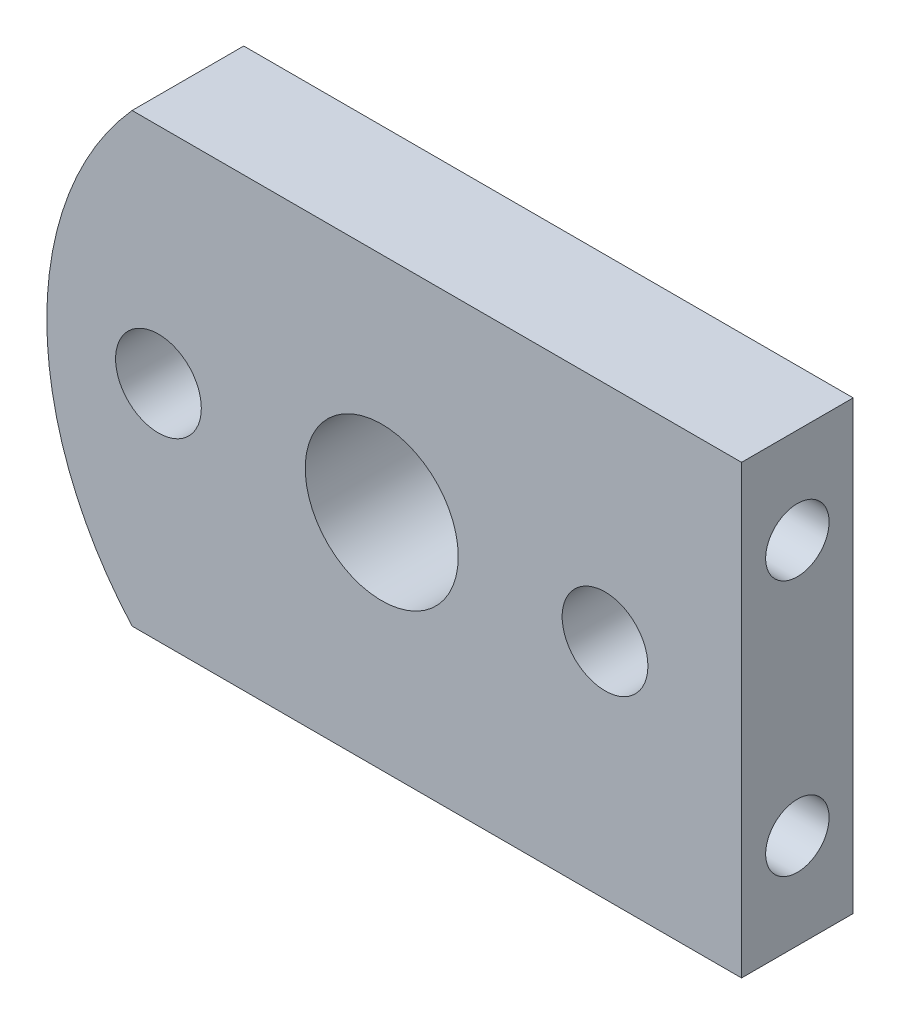
SolidWorks part; units mm, degrees
ref_plane "Front Plane" through (0, 0, 0) normal (0, 0, 1) x (1, 0, 0)
ref_plane "Top Plane" through (0, 0, 0) normal (0, 1, 0) x (1, 0, 0)
ref_plane "Right Plane" through (0, 0, 0) normal (1, 0, 0) x (0, 0, -1)
sketch "Sketch1" plane through (0, 0, 0) normal (0, 0, 1) x (1, 0, 0)
  line L1 (0, 0) -> (44.45, 0)
  line L2 (0, 0) -> (0, 23.0124)
  line L3 (0, 23.0124) -> (44.45, 23.0124)
  line L4 (44.45, 0) -> (44.45, 23.0124)
  dimension "D1" = 23.0124
  dimension "D2" = 44.45
extrude "Boss-Extrude1" add sketch "Sketch1" along normal blind 4.7625
hole_wizard "1/4 Clearance Hole1" positions "Sketch2" profile "Sketch4" hole size "1/4" standard "ANSI Inch" end condition through all
sketch "Sketch2" plane through (0, 0, 4.7625) normal (0, 0, 1) x (1, 0, 0)
  circle A0 centre (29.1015, 10.3124) radius 3.175 construction
  point P0 (29.1015, 10.3124)
  point P3 (0, 0)
sketch "Sketch4" plane through (29.1015, 10.3124, 4.7625) normal (1, 0, 0) x (0, -1, 0)
  line L0 (0, 0) -> (0, 4.7625)
  line L1 (0, 4.7625) -> (3.2639, 4.7625)
  line L2 (3.2639, 4.7625) -> (3.2639, 0)
  line L5 (3.2639, 0) -> (0, 0)
  line L11 (0, -6.35) -> (0, 107.95) construction
  dimension "Thru Hole Dia." = 6.5278
  dimension "Thru Hole Depth" = 4.7625
hole_wizard "#6 Clearance Hole1" positions "Sketch5" profile "Sketch6" hole size "#6" standard "ANSI Inch" end condition through all
sketch "Sketch5" plane through (0, 0, 4.7625) normal (0, 0, 1) x (1, 0, 0)
  line L0 (29.1015, 10.3124) -> (38.6265, 10.3124) construction
  line L2 (29.1015, 10.3124) -> (19.5765, 10.3124) construction
  point P1 (38.6265, 10.3124)
  point P7 (19.5765, 10.3124)
  dimension "D1" = 9.525
  dimension "D2" = 9.525
sketch "Sketch6" plane through (19.5765, 10.3124, 4.7625) normal (1, 0, 0) x (0, -1, 0)
  line L0 (0, 0) -> (0, 4.7625)
  line L1 (0, 4.7625) -> (1.8288, 4.7625)
  line L2 (1.8288, 4.7625) -> (1.8288, 0)
  line L5 (1.8288, 0) -> (0, 0)
  line L11 (0, -6.35) -> (0, 107.95) construction
  dimension "Thru Hole Dia." = 3.6576
  dimension "Thru Hole Depth" = 4.7625
sketch "Sketch7" plane through (0, 0, 4.7625) normal (0, 0, 1) x (1, 0, 0)
  line L0 (0, 19.8374) -> (44.45, 19.8374) construction
  line L1 (0, 23.0124) -> (0, 0) construction
  line L2 (44.45, 0) -> (44.45, 23.0124) construction
  line L3 (0, 0.7874) -> (44.45, 0.7874) construction
  line L4 (18.4522, 0.7874) -> (44.45, 0.7874)
  line L6 (18.4522, 19.8374) -> (44.45, 19.8374)
  line L7 (44.45, 19.8374) -> (44.45, 23.0124)
  line L8 (44.45, 23.0124) -> (0, 23.0124)
  line L9 (0, 23.0124) -> (0, 0)
  line L10 (0, 0) -> (44.45, 0)
  line L11 (44.45, 0) -> (44.45, 0.7874)
  arc A0 (18.4522, 19.8374) -> (18.4522, 0.7874) centre (29.1015, 10.3124) ccw
  dimension "D1" = 28.575
  dimension "D2" = 9.525
  dimension "D3" = 9.525
extrude "Cut-Extrude1" cut sketch "Sketch7" against normal through all
hole_wizard "Tap Drill for #6-32 Tap1" positions "Sketch9" profile "Sketch11" hole size "#6-32" standard "ANSI Inch"
sketch "Sketch9" plane through (44.45, 0, 0) normal (1, 0, 0) x (0, 0, -1)
  line L0 (-2.3812, 19.8374) -> (-2.3812, 0.7874) construction
  line L1 (0, 19.8374) -> (-4.7625, 19.8374) construction
  line L2 (0, 0.7874) -> (-4.7625, 0.7874) construction
  point P12 (-2.3812, 15.7734)
  point P14 (-2.3812, 4.8514)
  dimension "D1" = 4.064
  dimension "D2" = 4.064
sketch "Sketch11" plane through (44.45, 4.8514, 2.3812) normal (0, 1, 0) x (0, 0, -1)
  line L0 (0, 0) -> (0, 13.5127)
  line L1 (0, 13.5127) -> (1.3525, 12.7)
  line L2 (1.3525, 12.7) -> (1.3525, 0)
  line L5 (1.3525, 0) -> (0, 0)
  line L10 (0, 13.5127) -> (-1.3526, 12.7) construction
  line L11 (0, -6.35) -> (0, 107.95) construction
  dimension "Hole Dia." = 2.7051
  dimension "Hole Depth" = 12.7
  dimension "Drill Angle" = 118
sketch "Sketch8" plane through (0, 0, 4.7625) normal (0, 0, 1) x (1, 0, 0)
  line L0 (44.45, 15.7734) -> (15.8988, 15.7734) construction
  line L1 (44.45, 0.7874) -> (44.45, 19.8374) construction
  line L2 (33.02, 8.0899) -> (35.56, 1.6129) construction
  line L4 (18.4522, 19.8374) -> (44.45, 19.8374) construction
  line L5 (14.814, 10.3124) -> (44.45, 10.3124) construction
  line L6 (25.4, 13.9954) -> (33.02, 13.9954)
  line L7 (25.4, 13.9954) -> (25.4, 17.5514)
  line L8 (25.4, 17.5514) -> (33.02, 17.5514)
  line L9 (44.45, 13.9954) -> (44.45, 17.5514)
  line L10 (25.4, 13.9954) -> (44.45, 17.5514) construction
  line L11 (25.4, 17.5514) -> (44.45, 13.9954) construction
  line L12 (36.83, 17.5514) -> (39.37, 17.5514)
  line L13 (39.37, 13.9954) -> (36.83, 13.9954)
  line L14 (34.29, 13.9954) -> (34.29, 17.5514) construction
  line L15 (35.56, 17.5514) -> (36.83, 17.5514)
  line L16 (33.02, 19.0119) -> (35.56, 19.0119)
  line L17 (33.02, 19.0119) -> (33.02, 17.5514)
  line L18 (39.37, 13.9954) -> (44.45, 13.9954)
  line L19 (33.02, 12.5349) -> (35.56, 12.5349)
  line L20 (39.37, 17.5514) -> (44.45, 17.5514)
  line L21 (35.56, 19.0119) -> (35.56, 17.5514)
  line L22 (33.02, 19.0119) -> (35.56, 12.5349) construction
  line L23 (33.02, 12.5349) -> (35.56, 19.0119) construction
  line L24 (35.56, 13.9954) -> (36.83, 13.9954)
  line L25 (35.56, 13.9954) -> (35.56, 12.5349)
  line L26 (33.02, 13.9954) -> (33.02, 12.5349)
  line L27 (33.02, 1.6129) -> (35.56, 8.0899) construction
  line L28 (34.29, 6.6294) -> (34.29, 3.0734) construction
  line L29 (25.4, 3.0734) -> (44.45, 6.6294) construction
  line L30 (25.4, 6.6294) -> (44.45, 3.0734) construction
  line L31 (44.45, 4.8514) -> (15.8988, 4.8514) construction
  line L32 (33.02, 6.6294) -> (33.02, 8.0899)
  line L33 (35.56, 6.6294) -> (35.56, 8.0899)
  line L34 (35.56, 6.6294) -> (36.83, 6.6294)
  line L35 (35.56, 1.6129) -> (35.56, 3.0734)
  line L36 (39.37, 3.0734) -> (44.45, 3.0734)
  line L37 (33.02, 8.0899) -> (35.56, 8.0899)
  line L38 (39.37, 6.6294) -> (44.45, 6.6294)
  line L39 (33.02, 1.6129) -> (33.02, 3.0734)
  line L40 (33.02, 1.6129) -> (35.56, 1.6129)
  line L41 (35.56, 3.0734) -> (36.83, 3.0734)
  line L42 (39.37, 6.6294) -> (36.83, 6.6294)
  line L43 (36.83, 3.0734) -> (39.37, 3.0734)
  line L44 (44.45, 6.6294) -> (44.45, 3.0734)
  line L45 (25.4, 3.0734) -> (33.02, 3.0734)
  line L46 (25.4, 6.6294) -> (25.4, 3.0734)
  line L47 (25.4, 6.6294) -> (33.02, 6.6294)
  arc A0 (18.4522, 19.8374) -> (18.4522, 0.7874) centre (29.1015, 10.3124) ccw construction
  point P13 (34.925, 15.7734)
  point P18 (34.925, 15.7734)
  point P21 (34.29, 15.7734)
  point P52 (34.29, 4.8514)
  point P53 (34.925, 4.8514)
  dimension "D2" = 4.064
  dimension "D3" = 3.556
  dimension "D4" = 19.05
  dimension "D5" = 2.54
  dimension "D6" = 6.477
extrude "Cut-Extrude2" [suppressed] cut sketch "Sketch8" against normal through all
